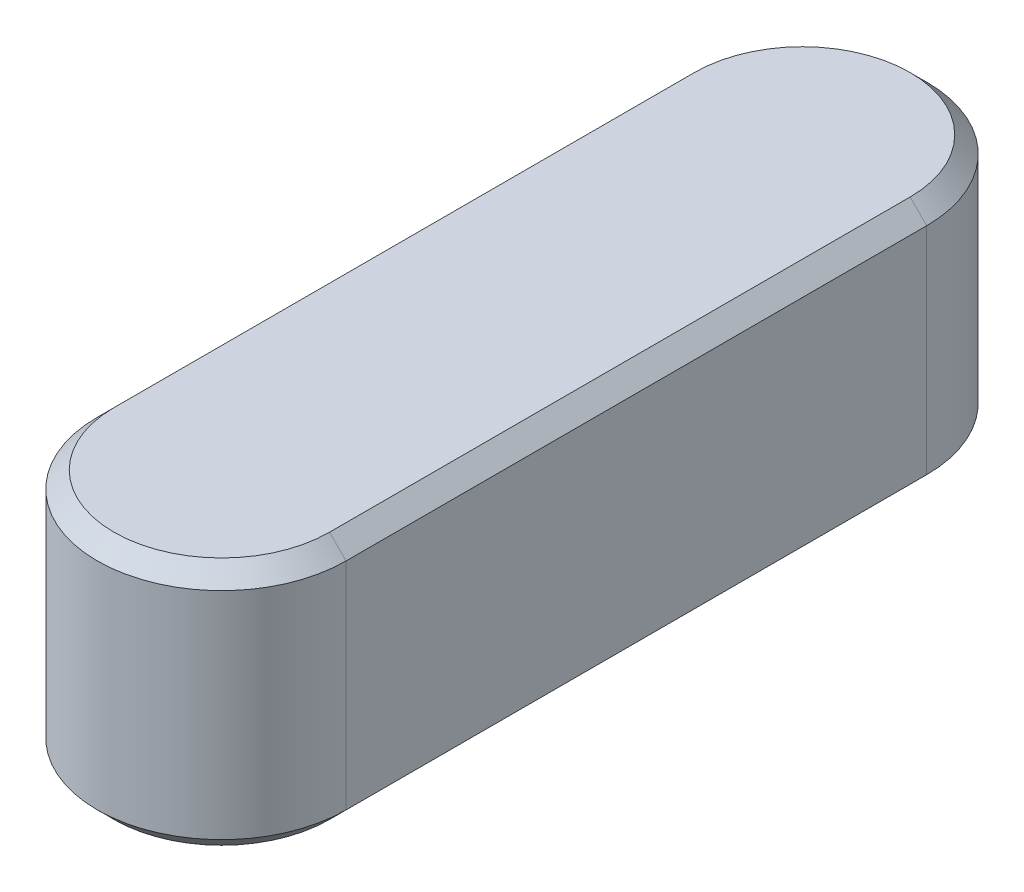
SolidWorks part; units mm, degrees
ref_plane "Front Plane" through (0, 0, 0) normal (0, 0, 1) x (1, 0, 0)
ref_plane "Top Plane" through (0, 0, 0) normal (0, 1, 0) x (1, 0, 0)
ref_plane "Right Plane" through (0, 0, 0) normal (1, 0, 0) x (0, 0, -1)
sketch "Sketch1" plane through (0, 0, 0) normal (0, 1, 0) x (1, 0, 0)
  line L0 (-24.9948, 23.2833) -> (-24.9948, 16.2833)
  line L1 (-27.9948, 23.2833) -> (-27.9948, 16.2833)
  arc A0 (-24.9948, 23.2833) -> (-27.9948, 23.2833) centre (-26.4948, 23.2833) ccw
  arc A1 (-27.9948, 16.2833) -> (-24.9948, 16.2833) centre (-26.4948, 16.2833) ccw
  dimension "D1" = 1.5
  dimension "D2" = 1.5
  dimension "D3" = 7
  dimension "D4" = 3
extrude "Extrude1" add sketch "Sketch1" along normal blind 3
chamfer "Chamfer1" distance 0.2 angle 45 8 edges at (-26.4948, 0, -24.7833) (-27.9948, 0, -19.7833) (-24.9948, 0, -19.7833) (-26.4948, 0, -14.7833) (-27.9948, 3, -19.7833) (-26.4948, 3, -14.7833) (-26.4948, 3, -24.7833) (-24.9948, 3, -19.7833)
